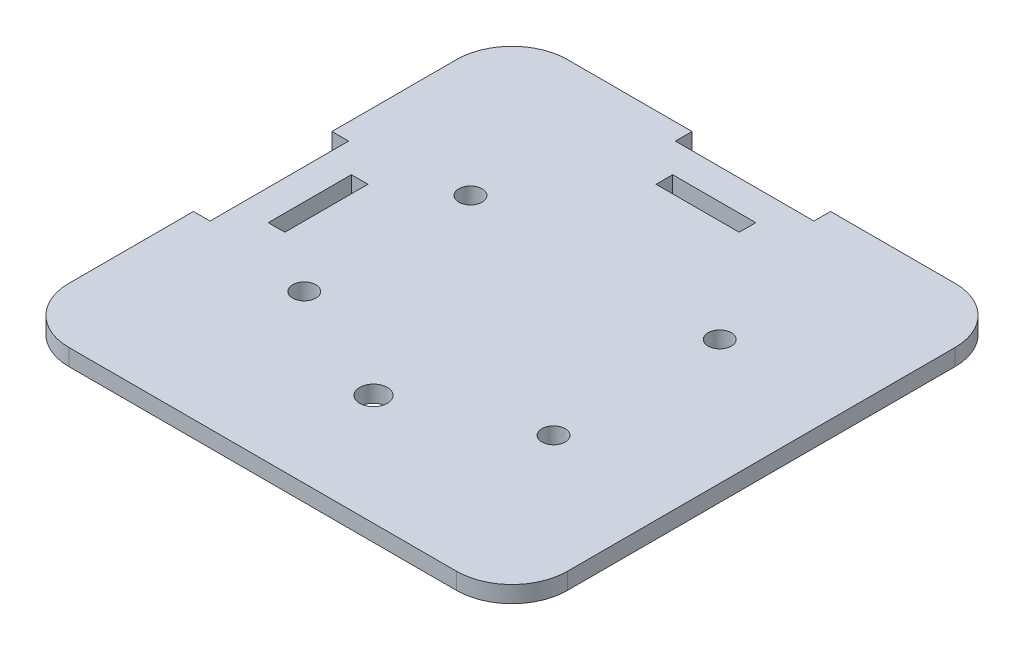
SolidWorks part; units mm, degrees
ref_plane "Front Plane" through (0, 0, 0) normal (0, 0, 1) x (1, 0, 0)
ref_plane "Top Plane" through (0, 0, 0) normal (0, 1, 0) x (1, 0, 0)
ref_plane "Right Plane" through (0, 0, 0) normal (1, 0, 0) x (0, 0, -1)
sketch "Sketch1" plane through (0, 0, 0) normal (0, 1, 0) x (1, 0, 0)
  line L1 (35, -45) -> (-35, -45)
  line L2 (45, -35) -> (45, 35)
  line L3 (35, 45) -> (-35, 45)
  line L4 (-45, -35) -> (-45, 35)
  line L5 (45, -45) -> (-45, 45) construction
  line L6 (45, 45) -> (-45, -45) construction
  line L7 (-45, 12.5) -> (-42, 12.5)
  line L8 (-45, 12.5) -> (-45, -12.5)
  line L9 (-45, -12.5) -> (-42, -12.5)
  line L10 (-42, 12.5) -> (-42, -12.5)
  line L11 (-12.5, 45) -> (12.5, 45)
  line L12 (-12.5, 45) -> (-12.5, 42)
  line L13 (-12.5, 42) -> (12.5, 42)
  line L14 (12.5, 45) -> (12.5, 42)
  arc A0 (-45, -35) -> (-35, -45) centre (-35, -35) ccw
  arc A1 (35, -45) -> (45, -35) centre (35, -35) ccw
  arc A2 (45, 35) -> (35, 45) centre (35, 35) ccw
  arc A3 (-45, 35) -> (-35, 45) centre (-35, 35) cw
  point P0 (0, 0)
  point P22 (-42, 0)
  point P23 (-45, 0)
  point P28 (0, 42)
  point P29 (0, 45)
  dimension "D1" = 10
  dimension "D2" = 3
  dimension "D3" = 25
  dimension "D4" = 0
  dimension "D5" = 3
  dimension "D6" = 25
  dimension "D7" = 0
  dimension "D8" = 90
  dimension "D9" = 90
extrude "Boss-Extrude1" add sketch "Sketch1" along normal blind 3 contours A3 L4 L7 L10 L9 A0 L1 A1 L2 A2 L3 L14 L13 L12
sketch "Sketch2" plane through (0, 3, 0) normal (0, 1, 0) x (1, 0, 0)
  line L0 (0, -1.65) -> (0, 1.65) construction
  line L1 (-1.65, 0) -> (1.65, 0) construction
  circle A0 centre (-22.5, 15) radius 2.1
  circle A1 centre (22.5, 15) radius 2.1
  circle A2 centre (22.5, -15) radius 2.1
  circle A3 centre (-22.5, -15) radius 2.1
  dimension "D1" = 22.5
  dimension "D2" = 15
extrude "Cut-Extrude1" cut sketch "Sketch2" against normal blind 3
sketch "Sketch3" plane through (0, 3, 0) normal (0, 1, 0) x (1, 0, 0)
  line L1 (7.5, 33.5) -> (-7.5, 33.5)
  line L2 (7.5, 33.5) -> (7.5, 36.5)
  line L3 (7.5, 36.5) -> (-7.5, 36.5)
  line L4 (-7.5, 33.5) -> (-7.5, 36.5)
  line L5 (7.5, 33.5) -> (-7.5, 36.5) construction
  line L6 (7.5, 36.5) -> (-7.5, 33.5) construction
  line L7 (-36.5, -7.5) -> (-33.5, -7.5)
  line L8 (-36.5, -7.5) -> (-36.5, 7.5)
  line L9 (-36.5, 7.5) -> (-33.5, 7.5)
  line L10 (-33.5, -7.5) -> (-33.5, 7.5)
  line L11 (-36.5, -7.5) -> (-33.5, 7.5) construction
  line L12 (-36.5, 7.5) -> (-33.5, -7.5) construction
  point P0 (0, 35)
  point P5 (-35, 0)
  dimension "D1" = 3
  dimension "D2" = 15
  dimension "D3" = 0
  dimension "D4" = 35
  dimension "D5" = 15
  dimension "D6" = 0
  dimension "D7" = 35
  dimension "D8" = 3
extrude "Cut-Extrude2" cut sketch "Sketch3" against normal blind 10
sketch "Sketch4" plane through (0, 3, 0) normal (0, 1, 0) x (1, 0, 0)
  circle A0 centre (0, -25) radius 2.5
  dimension "D1" = 25
extrude "Cut-Extrude3" cut sketch "Sketch4" against normal blind 14
